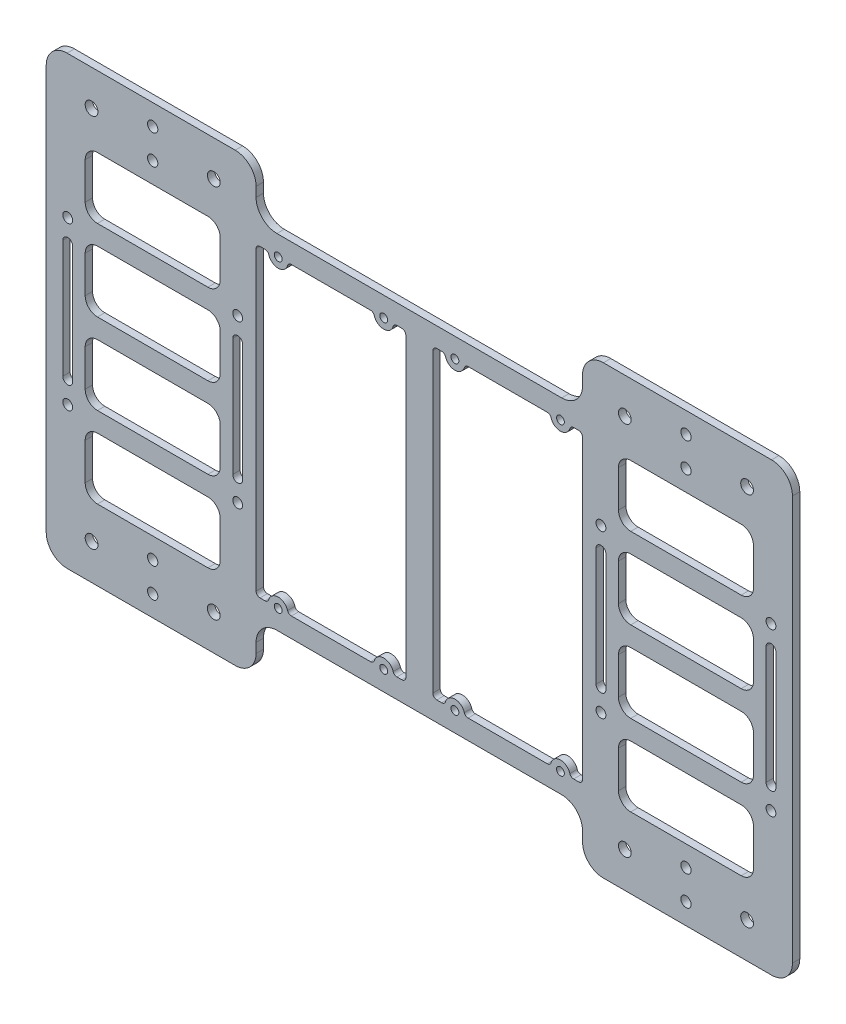
SolidWorks part; units mm, degrees
material "Thornel Mat VMA"
ref_plane "Front Plane" through (0, 0, 0) normal (0, 0, 1) x (1, 0, 0)
ref_plane "Top Plane" through (0, 0, 0) normal (0, 1, 0) x (1, 0, 0)
ref_plane "Right Plane" through (0, 0, 0) normal (1, 0, 0) x (0, 0, -1)
sketch "Model" plane through (0, 0, 0) normal (0, 0, 1) x (1, 0, 0)
  line L0 (-62.8666, 62) -> (-64.9, 62)
  line L1 (-66.5, 60.4) -> (-66.5, -60.4)
  line L2 (-64.9, -62) -> (-62.8666, -62)
  line L3 (-52.1334, 62) -> (-19.8666, 62)
  line L4 (-9.1334, 62) -> (-7.1, 62)
  line L5 (-5.5, 60.4) -> (-5.5, -60.4)
  line L6 (-7.1, -62) -> (-9.1334, -62)
  line L7 (-52.1334, -62) -> (-19.8666, -62)
  line L8 (9.1334, 62) -> (7.1, 62)
  line L9 (5.5, 60.4) -> (5.5, -60.4)
  line L10 (7.1, -62) -> (9.1334, -62)
  line L11 (19.8666, 62) -> (52.1334, 62)
  line L12 (62.8666, 62) -> (64.9, 62)
  line L13 (66.5, 60.4) -> (66.5, -60.4)
  line L14 (64.9, -62) -> (62.8666, -62)
  line L15 (19.8666, -62) -> (52.1334, -62)
  line L16 (-81.125, 24) -> (-81.125, 9)
  line L17 (-136.125, 24) -> (-136.125, 9)
  line L18 (-86.125, 4) -> (-131.125, 4)
  line L19 (-86.125, 29) -> (-131.125, 29)
  line L20 (-81.125, 57) -> (-81.125, 42)
  line L21 (-136.125, 57) -> (-136.125, 42)
  line L22 (-86.125, 37) -> (-131.125, 37)
  line L23 (-86.125, 62) -> (-131.125, 62)
  line L24 (-152, -82.4072) -> (-152, 82.4072)
  line L25 (152, -82.4072) -> (152, 82.4072)
  line L26 (-58, 70) -> (58, 70)
  line L27 (-58, -70) -> (58, -70)
  line L28 (-81.125, -24) -> (-81.125, -9)
  line L29 (-136.125, -24) -> (-136.125, -9)
  line L30 (-86.125, -4) -> (-131.125, -4)
  line L31 (-86.125, -29) -> (-131.125, -29)
  line L32 (-81.125, -57) -> (-81.125, -42)
  line L33 (-136.125, -57) -> (-136.125, -42)
  line L34 (-86.125, -37) -> (-131.125, -37)
  line L35 (-86.125, -62) -> (-131.125, -62)
  line L36 (81.125, 24) -> (81.125, 9)
  line L37 (136.125, 24) -> (136.125, 9)
  line L38 (86.125, 4) -> (131.125, 4)
  line L39 (86.125, 29) -> (131.125, 29)
  line L40 (81.125, 57) -> (81.125, 42)
  line L41 (136.125, 57) -> (136.125, 42)
  line L42 (86.125, 37) -> (131.125, 37)
  line L43 (86.125, 62) -> (131.125, 62)
  line L44 (81.125, -24) -> (81.125, -9)
  line L45 (136.125, -24) -> (136.125, -9)
  line L46 (86.125, -4) -> (131.125, -4)
  line L47 (86.125, -29) -> (131.125, -29)
  line L48 (81.125, -57) -> (81.125, -42)
  line L49 (136.125, -57) -> (136.125, -42)
  line L50 (86.125, -37) -> (131.125, -37)
  line L51 (86.125, -62) -> (131.125, -62)
  line L52 (-145.25, 24) -> (-145.25, -24)
  line L53 (-141.25, 24) -> (-141.25, -24)
  line L54 (-72, 24) -> (-72, -24)
  line L55 (-76, 24) -> (-76, -24)
  line L56 (145.25, 24) -> (145.25, -24)
  line L57 (141.25, 24) -> (141.25, -24)
  line L58 (72, 24) -> (72, -24)
  line L59 (76, 24) -> (76, -24)
  line L60 (-143.5, -90.9072) -> (-75, -90.9072)
  line L61 (-66.5, -82.4072) -> (-66.5, -78.5)
  line L62 (143.5, -90.9072) -> (75, -90.9072)
  line L63 (66.5, -82.4072) -> (66.5, -78.5)
  line L64 (-143.5, 90.9072) -> (-75, 90.9072)
  line L65 (-66.5, 82.4072) -> (-66.5, 78.5)
  line L66 (143.5, 90.9072) -> (75, 90.9072)
  line L67 (66.5, 82.4072) -> (66.5, 78.5)
  circle A0 centre (-57.5, 62) radius 1.6
  circle A1 centre (-14.5, 62) radius 1.6
  circle A2 centre (-57.5, -62) radius 1.6
  circle A3 centre (-14.5, -62) radius 1.6
  arc A4 (-61.3333, 60.8571) -> (-53.6667, 60.8571) centre (-57.5, 62) ccw
  arc A5 (-52.1334, 62) -> (-53.6667, 60.8571) centre (-52.1334, 60.4) ccw
  arc A6 (-61.3333, 60.8571) -> (-62.8666, 62) centre (-62.8666, 60.4) ccw
  arc A7 (-18.3333, 60.8571) -> (-10.6667, 60.8571) centre (-14.5, 62) ccw
  arc A8 (-9.1334, 62) -> (-10.6667, 60.8571) centre (-9.1334, 60.4) ccw
  arc A9 (-18.3333, 60.8571) -> (-19.8666, 62) centre (-19.8666, 60.4) ccw
  arc A10 (-53.6667, -60.8571) -> (-61.3333, -60.8571) centre (-57.5, -62) ccw
  arc A11 (-53.6667, -60.8571) -> (-52.1334, -62) centre (-52.1334, -60.4) ccw
  arc A12 (-62.8666, -62) -> (-61.3333, -60.8571) centre (-62.8666, -60.4) ccw
  arc A13 (-10.6667, -60.8571) -> (-18.3333, -60.8571) centre (-14.5, -62) ccw
  arc A14 (-10.6667, -60.8571) -> (-9.1334, -62) centre (-9.1334, -60.4) ccw
  arc A15 (-19.8666, -62) -> (-18.3333, -60.8571) centre (-19.8666, -60.4) ccw
  arc A16 (-66.5, -60.4) -> (-64.9, -62) centre (-64.9, -60.4) ccw
  arc A17 (-64.9, 62) -> (-66.5, 60.4) centre (-64.9, 60.4) ccw
  arc A18 (-7.1, -62) -> (-5.5, -60.4) centre (-7.1, -60.4) ccw
  arc A19 (-5.5, 60.4) -> (-7.1, 62) centre (-7.1, 60.4) ccw
  circle A20 centre (14.5, 62) radius 1.6
  circle A21 centre (57.5, 62) radius 1.6
  circle A22 centre (14.5, -62) radius 1.6
  circle A23 centre (57.5, -62) radius 1.6
  arc A24 (10.6667, 60.8571) -> (18.3333, 60.8571) centre (14.5, 62) ccw
  arc A25 (19.8666, 62) -> (18.3333, 60.8571) centre (19.8666, 60.4) ccw
  arc A26 (10.6667, 60.8571) -> (9.1334, 62) centre (9.1334, 60.4) ccw
  arc A27 (53.6667, 60.8571) -> (61.3333, 60.8571) centre (57.5, 62) ccw
  arc A28 (62.8666, 62) -> (61.3333, 60.8571) centre (62.8666, 60.4) ccw
  arc A29 (53.6667, 60.8571) -> (52.1334, 62) centre (52.1334, 60.4) ccw
  arc A30 (18.3333, -60.8571) -> (10.6667, -60.8571) centre (14.5, -62) ccw
  arc A31 (18.3333, -60.8571) -> (19.8666, -62) centre (19.8666, -60.4) ccw
  arc A32 (9.1334, -62) -> (10.6667, -60.8571) centre (9.1334, -60.4) ccw
  arc A33 (61.3333, -60.8571) -> (53.6667, -60.8571) centre (57.5, -62) ccw
  arc A34 (61.3333, -60.8571) -> (62.8666, -62) centre (62.8666, -60.4) ccw
  arc A35 (52.1334, -62) -> (53.6667, -60.8571) centre (52.1334, -60.4) ccw
  arc A36 (5.5, -60.4) -> (7.1, -62) centre (7.1, -60.4) ccw
  arc A37 (7.1, 62) -> (5.5, 60.4) centre (7.1, 60.4) ccw
  arc A38 (64.9, -62) -> (66.5, -60.4) centre (64.9, -60.4) ccw
  arc A39 (66.5, 60.4) -> (64.9, 62) centre (64.9, 60.4) ccw
  arc A40 (-81.125, 24) -> (-86.125, 29) centre (-86.125, 24) ccw
  arc A41 (-136.125, 9) -> (-131.125, 4) centre (-131.125, 9) ccw
  arc A42 (-86.125, 4) -> (-81.125, 9) centre (-86.125, 9) ccw
  arc A43 (-131.125, 29) -> (-136.125, 24) centre (-131.125, 24) ccw
  circle A44 centre (-143.25, 33) radius 2
  arc A45 (-81.125, 57) -> (-86.125, 62) centre (-86.125, 57) ccw
  arc A46 (-136.125, 42) -> (-131.125, 37) centre (-131.125, 42) ccw
  arc A47 (-86.125, 37) -> (-81.125, 42) centre (-86.125, 42) ccw
  arc A48 (-131.125, 62) -> (-136.125, 57) centre (-131.125, 57) ccw
  arc A49 (-143.5, 90.9072) -> (-152, 82.4072) centre (-143.5, 82.4072) ccw
  arc A50 (143.5, -90.9072) -> (152, -82.4072) centre (143.5, -82.4072) ccw
  arc A51 (58, 70) -> (66.5, 78.5) centre (58, 78.5) ccw
  arc A52 (-66.5, 78.5) -> (-58, 70) centre (-58, 78.5) ccw
  arc A53 (-58, -70) -> (-66.5, -78.5) centre (-58, -78.5) ccw
  arc A54 (-86.125, -29) -> (-81.125, -24) centre (-86.125, -24) ccw
  arc A55 (-131.125, -4) -> (-136.125, -9) centre (-131.125, -9) ccw
  arc A56 (-81.125, -9) -> (-86.125, -4) centre (-86.125, -9) ccw
  arc A57 (-136.125, -24) -> (-131.125, -29) centre (-131.125, -24) ccw
  arc A58 (-86.125, -62) -> (-81.125, -57) centre (-86.125, -57) ccw
  arc A59 (-131.125, -37) -> (-136.125, -42) centre (-131.125, -42) ccw
  arc A60 (-81.125, -42) -> (-86.125, -37) centre (-86.125, -42) ccw
  arc A61 (-136.125, -57) -> (-131.125, -62) centre (-131.125, -57) ccw
  arc A62 (86.125, 29) -> (81.125, 24) centre (86.125, 24) ccw
  arc A63 (131.125, 4) -> (136.125, 9) centre (131.125, 9) ccw
  arc A64 (81.125, 9) -> (86.125, 4) centre (86.125, 9) ccw
  arc A65 (136.125, 24) -> (131.125, 29) centre (131.125, 24) ccw
  arc A66 (86.125, 62) -> (81.125, 57) centre (86.125, 57) ccw
  arc A67 (131.125, 37) -> (136.125, 42) centre (131.125, 42) ccw
  arc A68 (81.125, 42) -> (86.125, 37) centre (86.125, 42) ccw
  arc A69 (136.125, 57) -> (131.125, 62) centre (131.125, 57) ccw
  arc A70 (81.125, -24) -> (86.125, -29) centre (86.125, -24) ccw
  arc A71 (136.125, -9) -> (131.125, -4) centre (131.125, -9) ccw
  arc A72 (86.125, -4) -> (81.125, -9) centre (86.125, -9) ccw
  arc A73 (131.125, -29) -> (136.125, -24) centre (131.125, -24) ccw
  arc A74 (81.125, -57) -> (86.125, -62) centre (86.125, -57) ccw
  arc A75 (136.125, -42) -> (131.125, -37) centre (131.125, -42) ccw
  arc A76 (86.125, -37) -> (81.125, -42) centre (86.125, -42) ccw
  arc A77 (131.125, -62) -> (136.125, -57) centre (131.125, -57) ccw
  circle A78 centre (-143.25, -33) radius 2
  arc A79 (-141.25, 24) -> (-145.25, 24) centre (-143.25, 24) ccw
  arc A80 (-145.25, -24) -> (-141.25, -24) centre (-143.25, -24) ccw
  circle A81 centre (-74, 33) radius 2
  circle A82 centre (-74, -33) radius 2
  arc A83 (-72, 24) -> (-76, 24) centre (-74, 24) ccw
  arc A84 (-76, -24) -> (-72, -24) centre (-74, -24) ccw
  circle A85 centre (143.25, 33) radius 2
  circle A86 centre (143.25, -33) radius 2
  arc A87 (145.25, 24) -> (141.25, 24) centre (143.25, 24) ccw
  arc A88 (141.25, -24) -> (145.25, -24) centre (143.25, -24) ccw
  circle A89 centre (74, 33) radius 2
  circle A90 centre (74, -33) radius 2
  arc A91 (76, 24) -> (72, 24) centre (74, 24) ccw
  arc A92 (72, -24) -> (76, -24) centre (74, -24) ccw
  circle A93 centre (-108.625, -70.4072) radius 2.1
  circle A94 centre (-83.725, -76.4072) radius 2.6
  circle A95 centre (-108.625, -82.4072) radius 2.1
  arc A96 (-152, -82.4072) -> (-143.5, -90.9072) centre (-143.5, -82.4072) ccw
  arc A97 (-75, -90.9072) -> (-66.5, -82.4072) centre (-75, -82.4072) ccw
  arc A98 (66.5, -78.5) -> (58, -70) centre (58, -78.5) ccw
  arc A99 (66.5, -82.4072) -> (75, -90.9072) centre (75, -82.4072) ccw
  arc A100 (-66.5, 82.4072) -> (-75, 90.9072) centre (-75, 82.4072) ccw
  arc A101 (152, 82.4072) -> (143.5, 90.9072) centre (143.5, 82.4072) ccw
  arc A102 (75, 90.9072) -> (66.5, 82.4072) centre (75, 82.4072) ccw
  circle A103 centre (108.625, -70.4072) radius 2.1
  circle A104 centre (108.625, -82.4072) radius 2.1
  circle A105 centre (-108.625, 70.4072) radius 2.1
  circle A106 centre (-108.625, 82.4072) radius 2.1
  circle A107 centre (108.625, 70.4072) radius 2.1
  circle A108 centre (108.625, 82.4072) radius 2.1
  circle A109 centre (-133.525, -76.4072) radius 2.6
  circle A110 centre (-83.725, 76.4072) radius 2.6
  circle A111 centre (-133.525, 76.4072) radius 2.6
  circle A112 centre (83.725, -76.4072) radius 2.6
  circle A113 centre (133.525, -76.4072) radius 2.6
  circle A114 centre (83.725, 76.4072) radius 2.6
  circle A115 centre (133.525, 76.4072) radius 2.6
extrude "Boss-Extrude1" add sketch "Model" along normal blind 3
